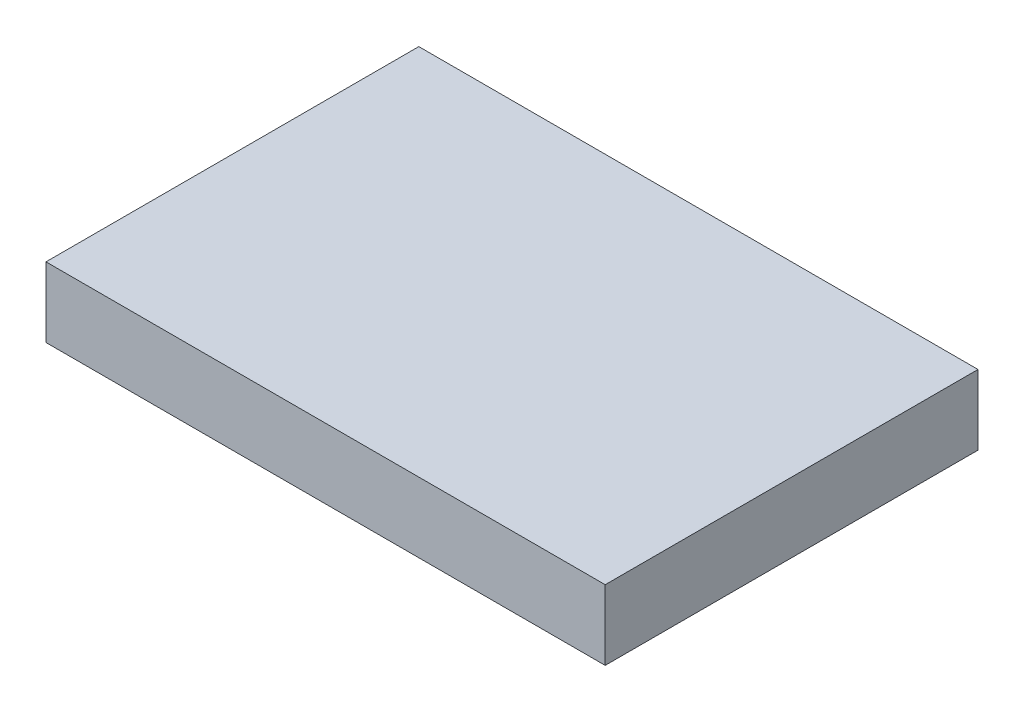
SolidWorks part; units mm, degrees
ref_plane "Front Plane" through (0, 0, 0) normal (0, 0, 1) x (1, 0, 0)
ref_plane "Top Plane" through (0, 0, 0) normal (0, 1, 0) x (1, 0, 0)
ref_plane "Right Plane" through (0, 0, 0) normal (1, 0, 0) x (0, 0, -1)
sketch "Sketch1" plane through (0, 0, 0) normal (0, 1, 0) x (1, 0, 0)
  line L1 (0, 0) -> (12, 0)
  line L2 (0, 0) -> (0, 8)
  line L3 (0, 8) -> (12, 8)
  line L4 (12, 0) -> (12, 8)
  dimension "D1" = 8
  dimension "D2" = 12
extrude "Boss-Extrude1" add sketch "Sketch1" along normal blind 1.5
